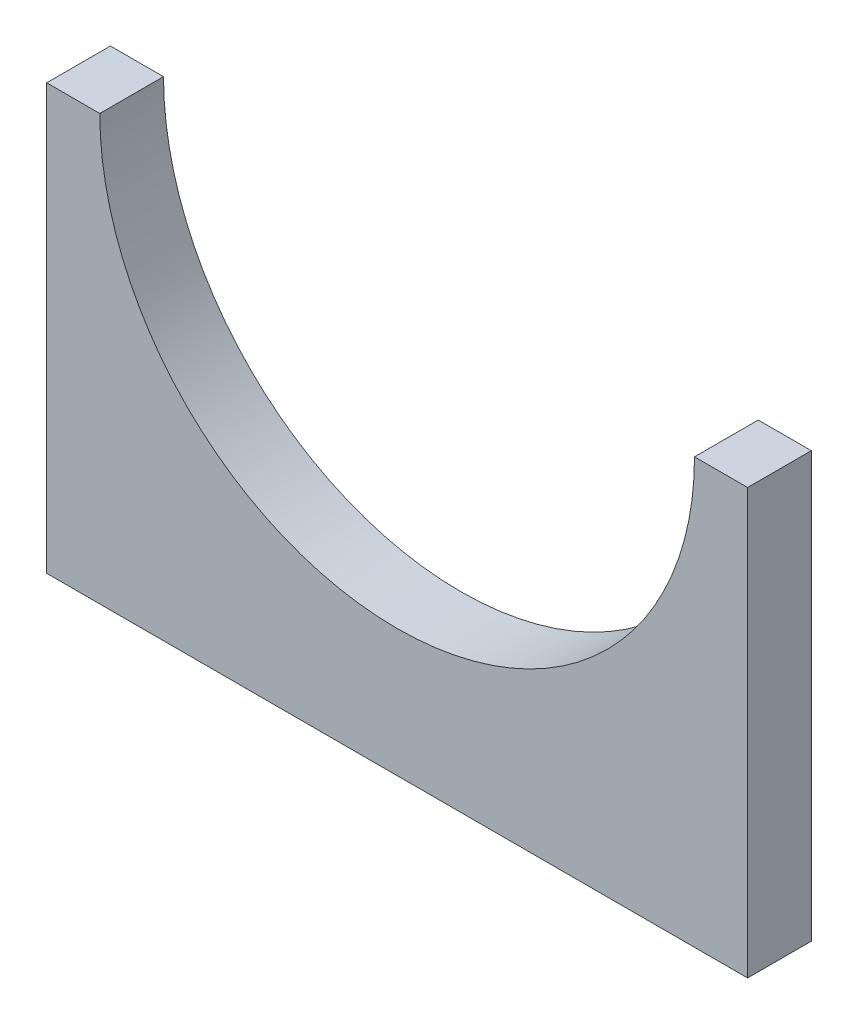
SolidWorks part; units mm, degrees
ref_plane "Front Plane" through (0, 0, 0) normal (0, 0, 1) x (1, 0, 0)
ref_plane "Top Plane" through (0, 0, 0) normal (0, 1, 0) x (1, 0, 0)
ref_plane "Right Plane" through (0, 0, 0) normal (1, 0, 0) x (0, 0, -1)
sketch "Sketch1" plane through (0, 0, 0) normal (0, 0, 1) x (1, 0, 0)
  line L0 (0, 16.6293) -> (0, -9.6904) construction
  line L1 (-16.5, 0) -> (-14, 0)
  line L2 (16.5, 0) -> (16.5, -20)
  line L3 (16.5, -20) -> (-16.5, -20)
  line L4 (-16.5, -20) -> (-16.5, 0)
  line L5 (14, 0) -> (16.5, 0)
  arc A0 (-14, 0) -> (14, 0) centre (0, 0) ccw
  dimension "D1" = 28
  dimension "D3" = 20
  dimension "D2" = 16.5
extrude "Boss-Extrude1" add sketch "Sketch1" along normal mid plane 3
